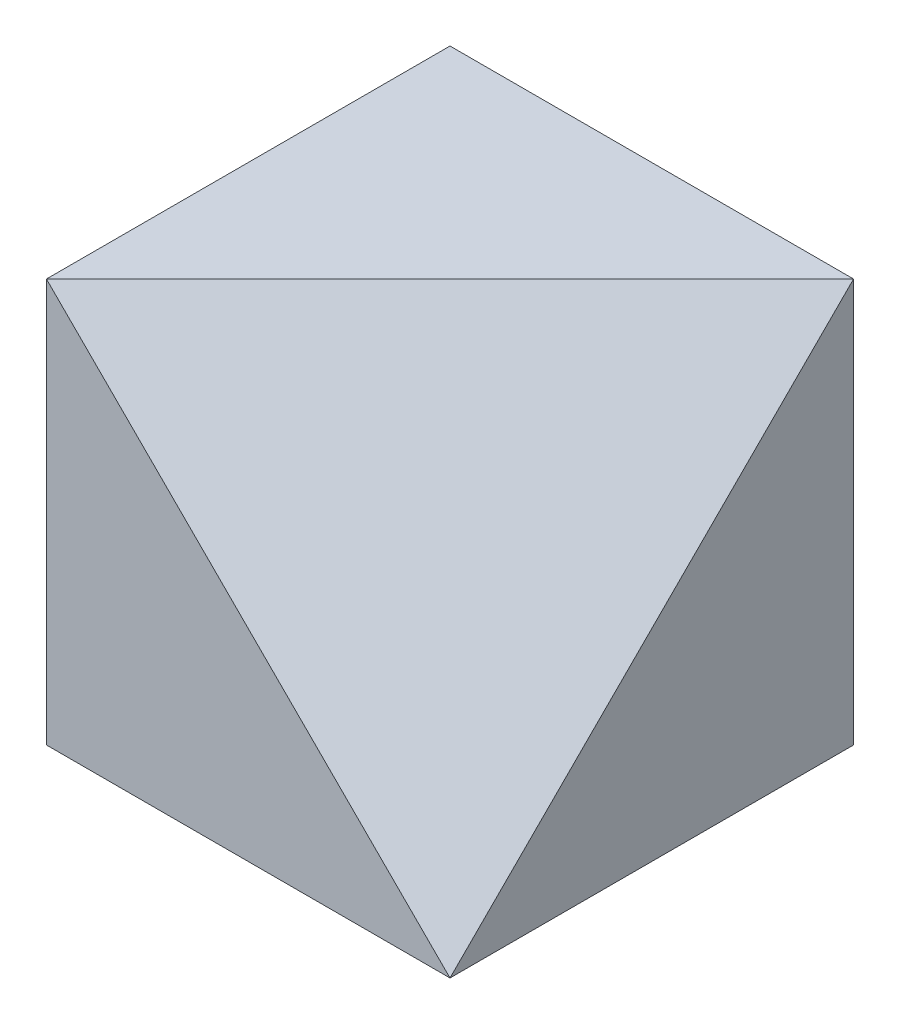
SolidWorks part; units mm, degrees
ref_plane "Front Plane" through (0, 0, 0) normal (0, 0, 1) x (1, 0, 0)
ref_plane "Top Plane" through (0, 0, 0) normal (0, 1, 0) x (1, 0, 0)
ref_plane "Right Plane" through (0, 0, 0) normal (1, 0, 0) x (0, 0, -1)
sketch "Sketch1" plane through (0, 0, 0) normal (0, 1, 0) x (1, 0, 0)
  line L1 (-40, 40) -> (40, 40)
  line L2 (-40, 40) -> (-40, -40)
  line L3 (-40, -40) -> (40, -40)
  line L4 (40, 40) -> (40, -40)
  line L5 (-40, 40) -> (40, -40) construction
  line L6 (-40, -40) -> (40, 40) construction
  point P0 (0, 0)
  dimension "D1" = 80
  dimension "D2" = 80
extrude "Boss-Extrude1" add sketch "Sketch1" along normal blind 80
sketch "Sketch2" plane through (0, 80, 0) normal (0, 1, 0) x (1, 0, 0)
  line L0 (-40, -40) -> (40, 40) construction
sketch "Sketch3" plane through (40, 0, 0) normal (1, 0, 0) x (0, 0, -1)
  line L0 (-40, 0) -> (40, 80) construction
sketch "Sketch4" plane through (0, 0, 40) normal (0, 0, 1) x (1, 0, 0)
  line L0 (-40, 80) -> (40, 0) construction
ref_plane "Plane1" through (26.6667, 26.6667, 26.6667) normal (0.5774, 0.5774, 0.5774) x (0.8165, -0.4082, -0.4082)
sketch "Sketch5" plane through (26.6667, 26.6667, 26.6667) normal (0.5774, 0.5774, 0.5774) x (0.8165, -0.4082, -0.4082)
  line L0 (-81.6497, 28.2843) -> (16.3299, -28.2843) construction
  line L1 (-81.6497, 28.2843) -> (16.3299, 84.8528) construction
  line L2 (16.3299, -28.2843) -> (16.3299, 84.8528) construction
  line L3 (-81.6497, 28.2843) -> (16.3299, -28.2843)
  line L4 (-81.6497, 28.2843) -> (16.3299, 84.8528)
  line L5 (16.3299, -28.2843) -> (16.3299, 84.8528)
extrude "Cut-Extrude1" cut sketch "Sketch5" along normal blind 80
sketch3d "3DSketch1"
  line L0 (40, 0, -40) -> (-40, 80, -40)
  line L1 (-40, 80, -40) -> (-40, 0, 40)
  line L2 (-40, 0, 40) -> (40, 0, -40)
ref_plane "Plane2" through (0, 0, 0) normal (0.5774, 0.5774, 0.5774) x (0.8165, -0.4082, -0.4082)
sketch "Sketch6" plane through (0, 0, 0) normal (0.5774, 0.5774, 0.5774) x (0.8165, -0.4082, -0.4082)
  line L0 (-48.9898, -28.2843) -> (48.9898, 28.2843) construction
  line L1 (-48.9898, 84.8528) -> (-48.9898, -28.2843) construction
  line L2 (48.9898, 28.2843) -> (-48.9898, 84.8528) construction
  line L3 (-48.9898, -28.2843) -> (48.9898, 28.2843)
  line L4 (-48.9898, 84.8528) -> (-48.9898, -28.2843)
  line L5 (48.9898, 28.2843) -> (-48.9898, 84.8528)
extrude "Cut-Extrude2" cut sketch "Sketch6" against normal blind 80
